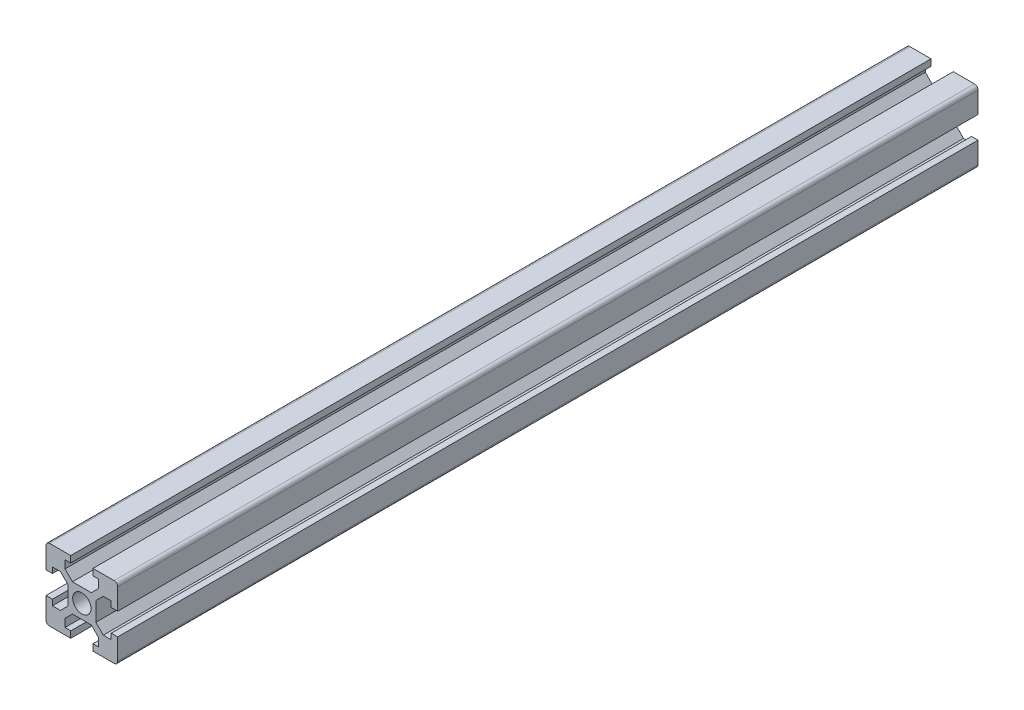
SolidWorks part; units mm, degrees
ref_plane "前视基准面" through (0, 0, 0) normal (0, 0, 1) x (1, 0, 0)
ref_plane "上视基准面" through (0, 0, 0) normal (0, 1, 0) x (1, 0, 0)
ref_plane "右视基准面" through (0, 0, 0) normal (1, 0, 0) x (0, 0, -1)
sketch "草图1" plane through (0, 0, 0) normal (0, 0, 1) x (1, 0, 0)
  line L0 (4.6219, 1.9053) -> (6.6947, 3.9781)
  line L1 (-8.0053, 8.0053) -> (-1.1053, 8.0053)
  line L2 (-8.0053, 8.0053) -> (-8.0053, 1.1053)
  line L3 (-8.0053, -11.9947) -> (-1.1053, -11.9947)
  line L4 (11.9947, 8.0053) -> (11.9947, 1.1053)
  line L5 (-8.0053, 8.0053) -> (11.9947, -11.9947) construction
  line L6 (5.8947, 0.6325) -> (7.9675, 2.7053)
  line L7 (-0.6325, -5.8947) -> (4.6219, -5.8947)
  line L8 (-1.9053, -4.6219) -> (-1.9053, 0.6325)
  line L9 (-0.6325, 1.9053) -> (4.6219, 1.9053)
  line L10 (5.8947, -4.6219) -> (5.8947, 0.6325)
  line L11 (-2.53, -6.5195) -> (5.8947, 1.9053) construction
  line L12 (-2.53, 2.53) -> (5.8947, -5.8947) construction
  line L13 (7.9675, 2.7053) -> (10.1947, 2.7053)
  line L14 (6.6947, 3.9781) -> (6.6947, 6.2053)
  line L15 (6.6947, 6.2053) -> (5.0947, 6.2053)
  line L16 (5.0947, 6.2053) -> (5.0947, 8.0053)
  line L17 (10.1947, 2.7053) -> (10.1947, 1.1053)
  line L18 (10.1947, 1.1053) -> (11.9947, 1.1053)
  line L19 (1.9947, -1.9947) -> (1.9947, 14.4959) construction
  line L20 (-6.2053, 1.1053) -> (-8.0053, 1.1053)
  line L21 (-6.2053, 2.7053) -> (-6.2053, 1.1053)
  line L22 (-1.9053, 0.6325) -> (-3.9781, 2.7053)
  line L23 (-3.9781, 2.7053) -> (-6.2053, 2.7053)
  line L24 (-2.7053, 3.9781) -> (-2.7053, 6.2053)
  line L25 (-0.6325, 1.9053) -> (-2.7053, 3.9781)
  line L26 (-2.7053, 6.2053) -> (-1.1053, 6.2053)
  line L27 (-1.1053, 6.2053) -> (-1.1053, 8.0053)
  line L28 (1.9947, -1.9947) -> (-12.4459, -1.9947) construction
  line L29 (-1.9053, -4.6219) -> (-3.9781, -6.6947)
  line L30 (-0.6325, -5.8947) -> (-2.7053, -7.9675)
  line L31 (4.6219, -5.8947) -> (6.6947, -7.9675)
  line L32 (5.8947, -4.6219) -> (7.9675, -6.6947)
  line L33 (-6.2053, -5.0947) -> (-8.0053, -5.0947)
  line L34 (10.1947, -5.0947) -> (11.9947, -5.0947)
  line L35 (-1.1053, -10.1947) -> (-1.1053, -11.9947)
  line L36 (5.0947, -10.1947) -> (5.0947, -11.9947)
  line L37 (-2.7053, -10.1947) -> (-1.1053, -10.1947)
  line L38 (-2.7053, -7.9675) -> (-2.7053, -10.1947)
  line L39 (-3.9781, -6.6947) -> (-6.2053, -6.6947)
  line L40 (-6.2053, -6.6947) -> (-6.2053, -5.0947)
  line L41 (10.1947, -6.6947) -> (10.1947, -5.0947)
  line L42 (6.6947, -10.1947) -> (5.0947, -10.1947)
  line L43 (6.6947, -7.9675) -> (6.6947, -10.1947)
  line L44 (7.9675, -6.6947) -> (10.1947, -6.6947)
  line L45 (11.9947, -5.0947) -> (11.9947, -11.9947)
  line L46 (5.0947, 8.0053) -> (11.9947, 8.0053)
  line L47 (-8.0053, -5.0947) -> (-8.0053, -11.9947)
  line L48 (5.0947, -11.9947) -> (11.9947, -11.9947)
  circle A0 centre (1.9947, -1.9947) radius 2.55
  point P0 (0, 0)
  point P6 (1.9947, -1.9947)
  dimension "D4" = 5.1
  dimension "D1" = 20
  dimension "D2" = 20
  dimension "D3" = 7.8
  dimension "D5" = 6.2
  dimension "D6" = 9.4
  dimension "D7" = 0.9
  dimension "D8" = 1.8
extrude "凸台-拉伸1" add sketch "草图1" along normal blind 240
fillet "圆角1" radius 1 4 edges at (11.9947, -11.9947, 120) (-8.0053, -11.9947, 120) (11.9947, 8.0053, 120) (-8.0053, 8.0053, 120)
